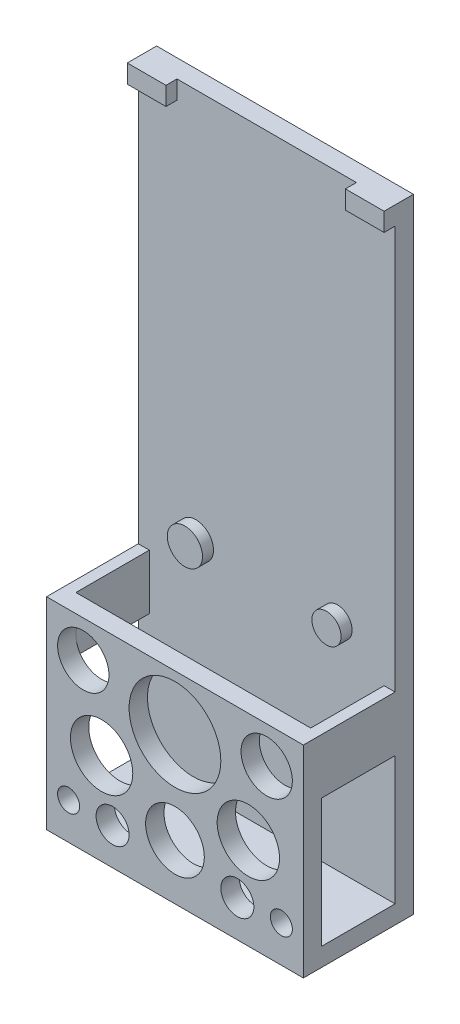
SolidWorks part; units mm, degrees
ref_plane "Front Plane" through (0, 0, 0) normal (0, 0, 1) x (1, 0, 0)
ref_plane "Top Plane" through (0, 0, 0) normal (0, 1, 0) x (1, 0, 0)
ref_plane "Right Plane" through (0, 0, 0) normal (1, 0, 0) x (0, 0, -1)
sketch "Sketch1" plane through (0, 0, 0) normal (0, 0, 1) x (1, 0, 0)
  line L1 (35, -85) -> (-35, -85)
  line L2 (35, -85) -> (35, 85)
  line L3 (35, 85) -> (-35, 85)
  line L4 (-35, -85) -> (-35, 85)
  line L5 (35, -85) -> (-35, 85) construction
  line L6 (35, 85) -> (-35, -85) construction
  point P0 (0, 0)
  dimension "D1" = 70
  dimension "D2" = 170
extrude "Boss-Extrude1" add sketch "Sketch1" along normal blind 5
sketch "Sketch2" plane through (0, 0, 5) normal (0, 0, 1) x (1, 0, 0)
  line L0 (35, -85) -> (35, 85) construction
  line L1 (-35, -85) -> (35, -85)
  line L2 (-35, -85) -> (-35, -80)
  line L3 (-35, -80) -> (35, -80)
  line L4 (35, -85) -> (35, -80)
  dimension "D1" = 5
extrude "Boss-Extrude2" add sketch "Sketch2" along normal blind 25
sketch "Sketch3" plane through (0, -80, 0) normal (0, 1, 0) x (1, 0, 0)
  line L0 (35, -30) -> (35, -5) construction
  line L1 (-35, -30) -> (35, -30)
  line L2 (-35, -30) -> (-35, -25)
  line L3 (-35, -25) -> (35, -25)
  line L4 (35, -30) -> (35, -25)
  dimension "D1" = 5
extrude "Boss-Extrude3" add sketch "Sketch3" along normal blind 50
sketch "Sketch4" plane through (0, 0, 5) normal (0, 0, 1) x (1, 0, 0)
  line L0 (0, 0) -> (0, -50000) construction
  line L1 (-35, -30) -> (-32, -30)
  line L2 (-35, -30) -> (-35, -45)
  line L3 (-35, -45) -> (-32, -45)
  line L4 (-32, -30) -> (-32, -45)
  line L5 (35, -30) -> (32, -30)
  line L6 (35, -30) -> (35, -45)
  line L7 (35, -45) -> (32, -45)
  line L8 (32, -30) -> (32, -45)
  dimension "D1" = 15
  dimension "D2" = 3
extrude "Boss-Extrude4" add sketch "Sketch4" along normal up to surface (20 mm away) up to face at (0, -55, 25)
sketch "Sketch6" plane through (0, 0, 30) normal (0, 0, 1) x (1, 0, 0)
  line L0 (0, 0) -> (0, -50000) construction
  line L1 (-35, -30) -> (35, -30) construction
  circle A0 centre (0, -45) radius 12.5
  circle A1 centre (-25, -40) radius 7
  circle A2 centre (25, -40) radius 7
  circle A3 centre (-20, -60) radius 8.5
  circle A4 centre (20, -60) radius 8.5
  circle A5 centre (0, -70) radius 8
  circle A6 centre (-17, -75) radius 4.5
  circle A7 centre (17, -75) radius 4.5
  circle A8 centre (29, -75) radius 3
  circle A9 centre (-29, -75) radius 3
  point P28 (27.6644, -29.1234)
  dimension "D3" = 14
  dimension "D4" = 25
  dimension "D6" = 6
  dimension "D10" = 17
  dimension "D13" = 16
  dimension "D14" = 9
  dimension "D1" = 50
  dimension "D2" = 10
  dimension "D5" = 15
  dimension "D7" = 58
  dimension "D8" = 45
  dimension "D9" = 40
  dimension "D11" = 30
  dimension "D12" = 40
  dimension "D15" = 45
  dimension "D16" = 34
extrude "Cut-Extrude1" cut sketch "Sketch6" against normal up to next
sketch "Sketch7" plane through (0, 0, 5) normal (0, 0, 1) x (1, 0, 0)
  line L0 (0, 0) -> (0, 50000) construction
  line L1 (-35, 85) -> (-24.4507, 85)
  line L2 (-35, 85) -> (-35, 79.9859)
  line L3 (-35, 79.9859) -> (-24.4507, 79.9859)
  line L4 (-24.4507, 85) -> (-24.4507, 79.9859)
  line L5 (35, 85) -> (24.4507, 85)
  line L6 (35, 85) -> (35, 79.9859)
  line L7 (35, 79.9859) -> (24.4507, 79.9859)
  line L8 (24.4507, 85) -> (24.4507, 79.9859)
  circle A0 centre (-19.2947, -21.258) radius 4.7978
  circle A1 centre (19.2947, -21.258) radius 3.9875
extrude "Boss-Extrude5" add sketch "Sketch7" along normal blind 3
